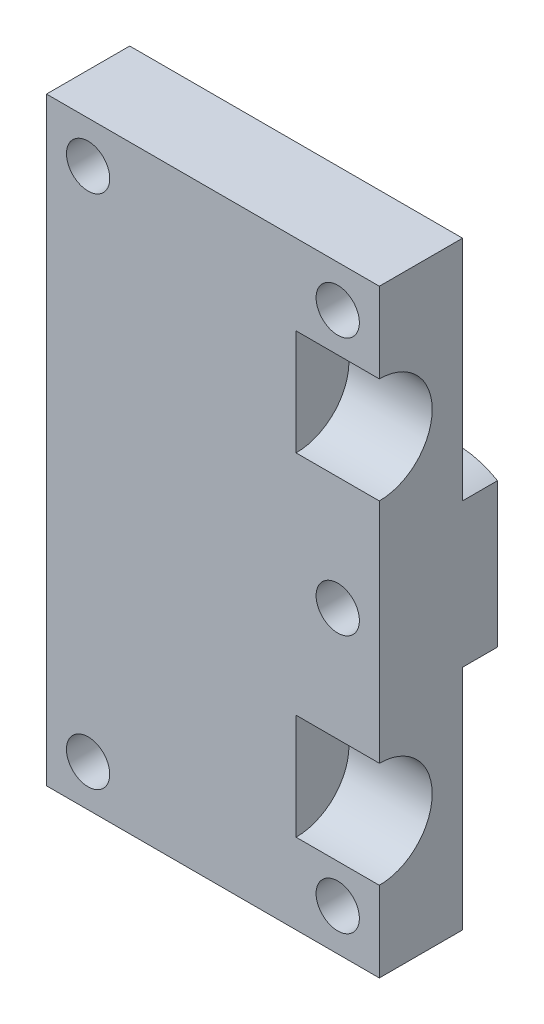
SolidWorks part; units mm, degrees
ref_plane "Front Plane" through (0, 0, 0) normal (0, 0, 1) x (1, 0, 0)
ref_plane "Top Plane" through (0, 0, 0) normal (0, 1, 0) x (1, 0, 0)
ref_plane "Right Plane" through (0, 0, 0) normal (1, 0, 0) x (0, 0, -1)
sketch "Sketch1" plane through (0, 0, 0) normal (0, 1, 0) x (1, 0, 0)
  line L1 (0, 0) -> (40, 0)
  line L2 (0, 0) -> (0, 10)
  line L3 (0, 10) -> (40, 10)
  line L4 (40, 0) -> (40, 10)
  dimension "D1" = 40
  dimension "D2" = 10
extrude "Boss-Extrude1" add sketch "Sketch1" along normal mid plane 72
sketch "Sketch2" plane through (40, 0, 0) normal (1, 0, 0) x (0, 0, -1)
  line L0 (0, 36) -> (0, -36) construction
  line L1 (0, 36) -> (10, 36) construction
  line L4 (0, 26.35) -> (0, 13.65)
  line L5 (0, -13.65) -> (0, -26.35)
  arc A0 (0, 13.65) -> (0, 26.35) centre (0, 20) ccw
  arc A1 (0, -26.35) -> (0, -13.65) centre (0, -20) ccw
  dimension "D1" = 12.7
  dimension "D2" = 12.7
  dimension "D3" = 40
  dimension "D4" = 16
extrude "Cut-Extrude1" cut sketch "Sketch2" against normal blind 10
sketch "Sketch3" plane through (0, 0, -10) normal (0, 0, -1) x (-1, 0, 0)
  line L0 (-40, 36) -> (0, 36) construction
  line L1 (-40, 36) -> (-40, -36) construction
  line L2 (0, 36) -> (0, -36) construction
  line L3 (-40, -36) -> (0, -36) construction
  circle A0 centre (-35, 31) radius 2.6
  circle A1 centre (-5, 31) radius 2.6
  circle A2 centre (-35, -31) radius 2.6
  circle A3 centre (-5, -31) radius 2.6
  circle A4 centre (-35, 0) radius 2.6
  dimension "D1" = 5.2
  dimension "D4" = 5.2
  dimension "D7" = 5.2
  dimension "D10" = 5.2
  dimension "D13" = 5.2
  dimension "D2" = 5
  dimension "D3" = 5
  dimension "D5" = 5
  dimension "D6" = 5
  dimension "D8" = 5
  dimension "D9" = 5
  dimension "D11" = 5
  dimension "D12" = 5
  dimension "D14" = 5
extrude "Cut-Extrude2" cut sketch "Sketch3" against normal through all
sketch "Sketch5" plane through (0, 0, -10) normal (0, 0, -1) x (-1, 0, 0)
  line L1 (-40, 8.6603) -> (-40, -8.6603)
  line L2 (-40, 36) -> (-40, -36) construction
  arc A0 (-40, -8.6603) -> (-40, 8.6603) centre (-35, 0) ccw
  circle A1 centre (-35, 0) radius 2.6 construction
  circle A2 centre (-35, 0) radius 2.6
  dimension "D1" = 0
  dimension "D2" = 20
  dimension "D3" = 0
extrude "Boss-Extrude2" add sketch "Sketch5" along normal blind 4.2
equation "\"D4@Sketch3\"=\"D1@Sketch3\""
equation "\"D5@Sketch3\"=\"D3@Sketch3\""
equation "\"D2@Sketch3\"=\"D3@Sketch3\""
equation "\"D6@Sketch3\"=\"D3@Sketch3\""
equation "\"D7@Sketch3\"=\"D1@Sketch3\""
equation "\"D8@Sketch3\"=\"D3@Sketch3\""
equation "\"D9@Sketch3\"=\"D3@Sketch3\""
equation "\"D10@Sketch3\"=\"D1@Sketch3\""
equation "\"D11@Sketch3\"=\"D3@Sketch3\""
equation "\"D12@Sketch3\"=\"D3@Sketch3\""
equation "\"D13@Sketch3\"=\"D1@Sketch3\""
equation "\"D14@Sketch3\"=\"D3@Sketch3\""
